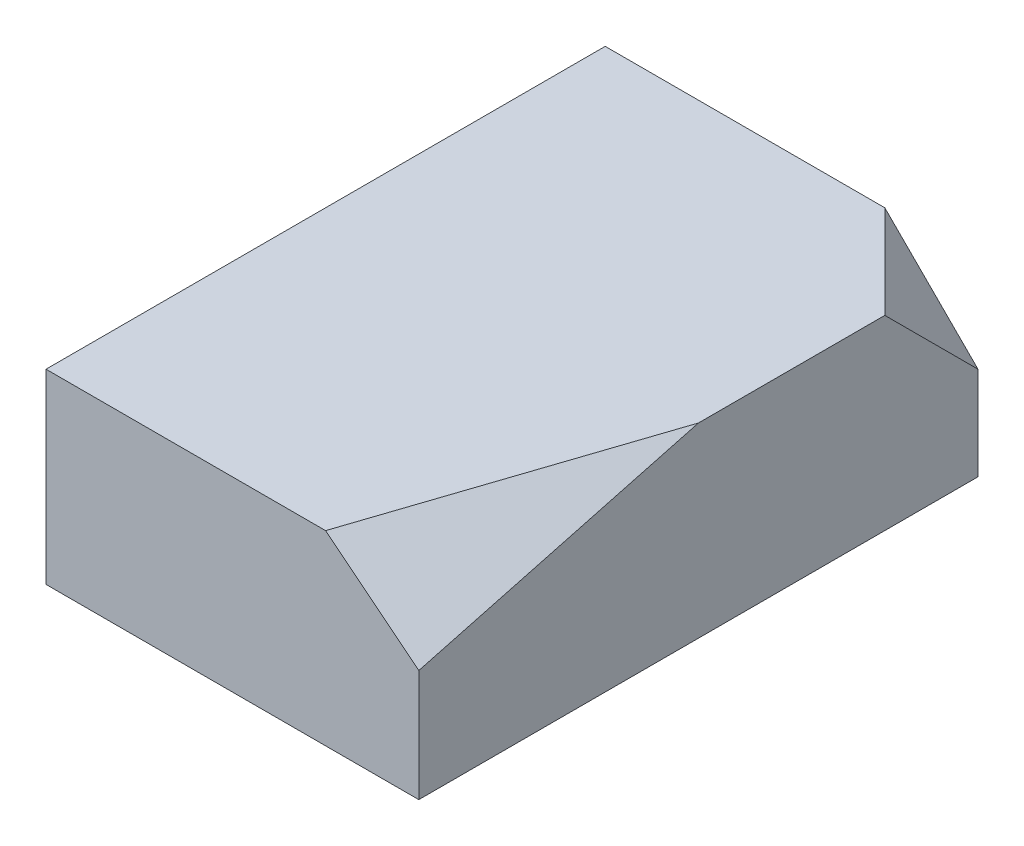
SolidWorks part; units mm, degrees
material "Cast Alloy Steel"
ref_plane "Front Plane" through (0, 0, 0) normal (0, 0, 1) x (1, 0, 0)
ref_plane "Top Plane" through (0, 0, 0) normal (0, 1, 0) x (1, 0, 0)
ref_plane "Right Plane" through (0, 0, 0) normal (1, 0, 0) x (0, 0, -1)
sketch "Sketch1" plane through (0, 0, 0) normal (0, 1, 0) x (1, 0, 0)
  line L1 (-50.8, -76.2) -> (50.8, -76.2)
  line L2 (-50.8, -76.2) -> (-50.8, 76.2)
  line L3 (-50.8, 76.2) -> (50.8, 76.2)
  line L4 (50.8, -76.2) -> (50.8, 76.2)
  line L5 (-50.8, -76.2) -> (50.8, 76.2) construction
  line L6 (-50.8, 76.2) -> (50.8, -76.2) construction
  point P0 (0, 0)
  dimension "D1" = 101.6
  dimension "D2" = 152.4
extrude "Boss-Extrude2" add sketch "Sketch1" along normal blind 50.8
sketch "Sketch4" plane through (50.8, 0, 0) normal (1, 0, 0) x (0, 0, -1)
  line L0 (-76.2, 30.48) -> (0, 50.8)
  line L1 (-76.2, 50.8) -> (-76.2, 0) construction
  line L2 (-76.2, 50.8) -> (76.2, 50.8) construction
  line L3 (76.2, 50.8) -> (76.2, 0) construction
  point P8 (-76.2, 50.8)
  point P9 (0, 0)
  dimension "D1" = 20.32
  dimension "D2" = 76.2
ref_point "Point1" parameters "D1"=76.2
ref_plane "Plane2" through (42.7512, 53.439, 14.2504) normal (0.6116, 0.7645, 0.2039) x (0.7912, -0.5909, -0.1576)
sketch "Sketch5" plane through (42.7512, 53.439, 14.2504) normal (0.6116, 0.7645, 0.2039) x (0.7912, -0.5909, -0.1576)
  line L0 (-21.9306, -60.5378) -> (10.1731, 13.0893)
  line L1 (10.1731, 13.0893) -> (10.1731, -65.7735)
  line L2 (10.1731, -65.7735) -> (-21.9306, -60.5378)
extrude "Cut-Extrude1" cut sketch "Sketch5" along normal through all
sketch "Sketch6" plane through (50.8, 0, 0) normal (1, 0, 0) x (0, 0, -1)
  line L0 (76.2, 25.4) -> (50.8, 50.8)
  line L1 (76.2, 50.8) -> (76.2, 0) construction
  line L2 (0, 50.8) -> (76.2, 50.8) construction
  dimension "D1" = 25.4
  dimension "D2" = 25.4
ref_point "Point2" parameters "D1"=25.4
ref_plane "Plane3" through (50.8, 50.8, -50.8) normal (-0.5774, -0.5774, 0.5774) x (0.8165, -0.4082, 0.4082)
sketch "Sketch7" plane through (50.8, 50.8, -50.8) normal (-0.5774, -0.5774, 0.5774) x (0.8165, -0.4082, 0.4082)
  line L0 (0, 0) -> (0, -35.921)
  line L1 (0, -35.921) -> (-31.1085, -17.9605)
  line L2 (-31.1085, -17.9605) -> (0, 0)
extrude "Cut-Extrude2" cut sketch "Sketch7" against normal through all
